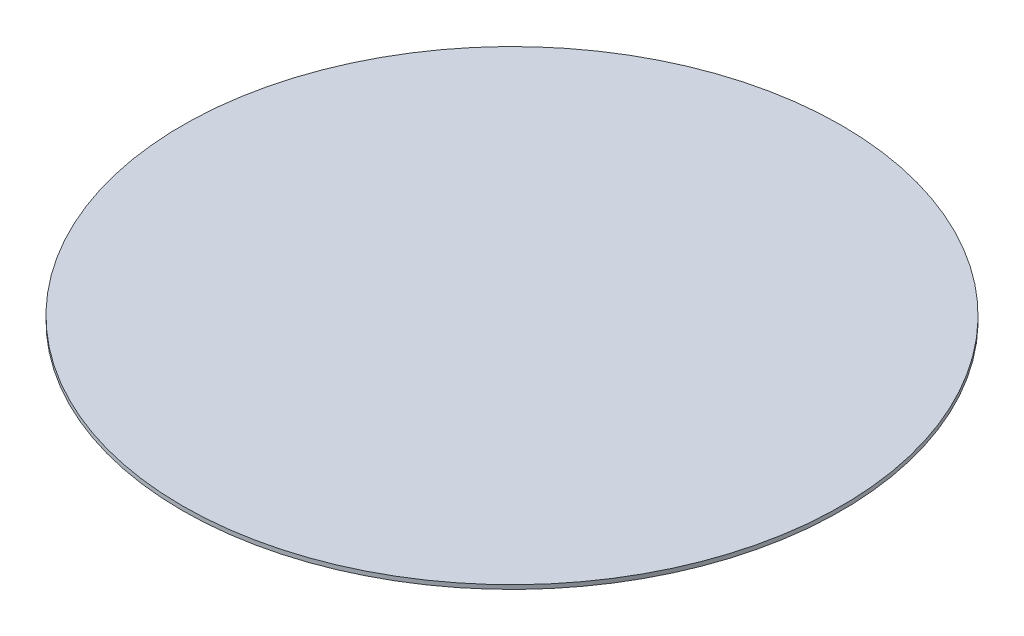
SolidWorks part; units mm, degrees
ref_plane "Front Plane" through (0, 0, 0) normal (0, 0, 1) x (1, 0, 0)
ref_plane "Top Plane" through (0, 0, 0) normal (0, 1, 0) x (1, 0, 0)
ref_plane "Right Plane" through (0, 0, 0) normal (1, 0, 0) x (0, 0, -1)
sketch "Sketch1" plane through (0, 0, 0) normal (0, 1, 0) x (1, 0, 0)
  circle A0 centre (0, 0) radius 80
  dimension "D1" = 160
extrude "Boss-Extrude1" add sketch "Sketch1" along normal blind 1
